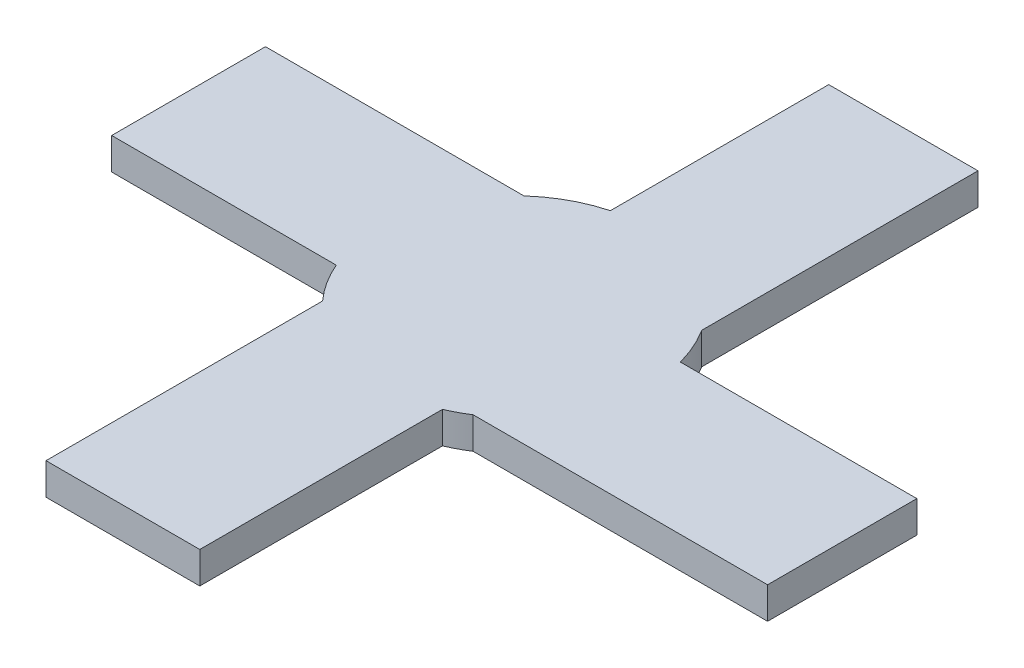
SolidWorks part; units mm, degrees
ref_plane "Front Plane" through (0, 0, 0) normal (0, 0, 1) x (1, 0, 0)
ref_plane "Top Plane" through (0, 0, 0) normal (0, 1, 0) x (1, 0, 0)
ref_plane "Right Plane" through (0, 0, 0) normal (1, 0, 0) x (0, 0, -1)
sketch "Sketch1" plane through (0, 0, 0) normal (0, 1, 0) x (1, 0, 0)
  line L0 (-77.26, -11.74) -> (-77.26, 22.26)
  line L1 (-77.26, 22.26) -> (-7.74, 22.26)
  line L2 (-7.74, 22.26) -> (-7.74, 77.26)
  line L3 (-7.74, 77.26) -> (25.26, 77.26)
  line L4 (25.26, 77.26) -> (25.26, 7.74)
  line L5 (25.26, 7.74) -> (81.26, 7.74)
  line L6 (81.26, 7.74) -> (81.26, -25.26)
  line L7 (81.26, -25.26) -> (11.74, -25.26)
  line L8 (11.74, -25.26) -> (11.74, -81.26)
  line L9 (11.74, -81.26) -> (-22.26, -81.26)
  line L10 (-22.26, -81.26) -> (-22.26, -11.74)
  line L11 (-22.26, -11.74) -> (-77.26, -11.74)
  line L12 (-1.65, 1.3) -> (1.65, 1.3)
  line L13 (1.65, -1.3) -> (-1.65, -1.3)
  arc A0 (-1.65, 1.3) -> (-1.65, -1.3) centre (-0.35, 0) ccw
  arc A1 (1.65, 1.3) -> (1.65, -1.3) centre (0.35, 0) cw
  point P19 (81.26, -8.76)
  dimension "D1" = 11.74
  dimension "D2" = 7.74
  dimension "D3" = 25.26
  dimension "D4" = 7.74
  dimension "D5" = 11.74
  dimension "D6" = 25.26
  dimension "D7" = 22.26
  dimension "D8" = 22.26
  dimension "D9" = 55
  dimension "D10" = 3.3
  dimension "D11" = 2.6
  dimension "D12" = 158.52
extrude "Boss-Extrude1" add sketch "Sketch1" along normal blind 7
sketch "Sketch2" plane through (0, 0, 0) normal (0, 1, 0) x (1, 0, 0)
  circle A0 centre (0, 0) radius 30
  dimension "D1" = 60
extrude "Boss-Extrude2" add sketch "Sketch2" along normal blind 7
